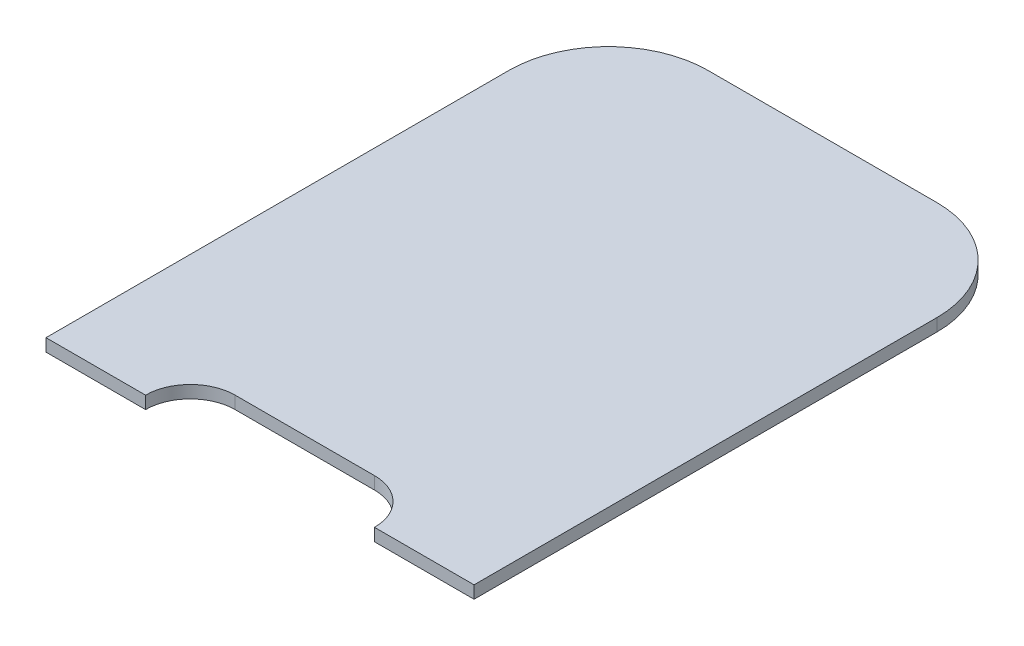
SolidWorks part; units mm, degrees
ref_plane "Front Plane" through (0, 0, 0) normal (0, 0, 1) x (1, 0, 0)
ref_plane "Top Plane" through (0, 0, 0) normal (0, 1, 0) x (1, 0, 0)
ref_plane "Right Plane" through (0, 0, 0) normal (1, 0, 0) x (0, 0, -1)
sketch "Sketch2" plane through (0, 0, 0) normal (0, 1, 0) x (1, 0, 0)
  line L0 (0, 0) -> (12.7, 0)
  line L2 (18.415, 5.715) -> (36.195, 5.715)
  line L4 (41.91, 0) -> (54.61, 0)
  line L5 (54.61, 0) -> (54.61, 59.055)
  line L6 (41.91, 71.755) -> (12.7, 71.755)
  line L7 (0, 59.055) -> (0, 0)
  arc A0 (41.91, 71.755) -> (54.61, 59.055) centre (41.91, 59.055) cw
  arc A1 (12.7, 71.755) -> (0, 59.055) centre (12.7, 59.055) ccw
  arc A2 (18.415, 5.715) -> (12.7, 0) centre (18.415, 0) ccw
  arc A3 (36.195, 5.715) -> (41.91, 0) centre (36.195, 0) cw
  dimension "D5" = 12.7
  dimension "D1" = 12.7
  dimension "D2" = 12.7
  dimension "D3" = 5.715
  dimension "D4" = 71.755
  dimension "D6" = 29.21
extrude "Boss-Extrude1" add sketch "Sketch2" along normal blind 1.6
